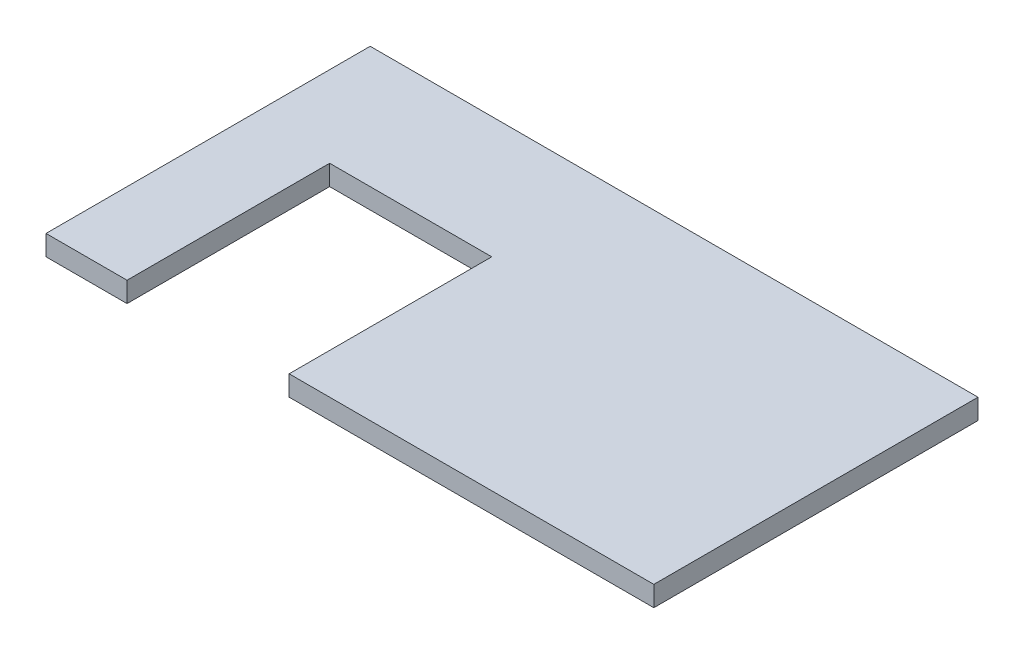
SolidWorks part; units mm, degrees
ref_plane "Front Plane" through (0, 0, 0) normal (0, 0, 1) x (1, 0, 0)
ref_plane "Top Plane" through (0, 0, 0) normal (0, 1, 0) x (1, 0, 0)
ref_plane "Right Plane" through (0, 0, 0) normal (1, 0, 0) x (0, 0, -1)
sketch "Sketch1" plane through (0, 0, 0) normal (0, 1, 0) x (1, 0, 0)
  line L0 (-15, -40) -> (75, -40)
  line L1 (-75, -40) -> (-55, -40)
  line L2 (-75, -40) -> (-75, 40)
  line L3 (-75, 40) -> (75, 40)
  line L4 (75, -40) -> (75, 40)
  line L5 (-75, -40) -> (-55, -29.3333) construction
  line L6 (-75, 40) -> (75, -40) construction
  line L12 (-55, -40) -> (-55, 10)
  line L13 (-55, 10) -> (-15, 10)
  line L14 (-15, -40) -> (-15, 10)
  line L15 (-15, -8) -> (75, 40) construction
  point P0 (0, 0)
  point P10 (-209.8525, 66.7886)
  dimension "D1" = 150
  dimension "D2" = 80
  dimension "D3" = 40
  dimension "D4" = 20
  dimension "D5" = 50
extrude "Boss-Extrude1" add sketch "Sketch1" along normal blind 5
